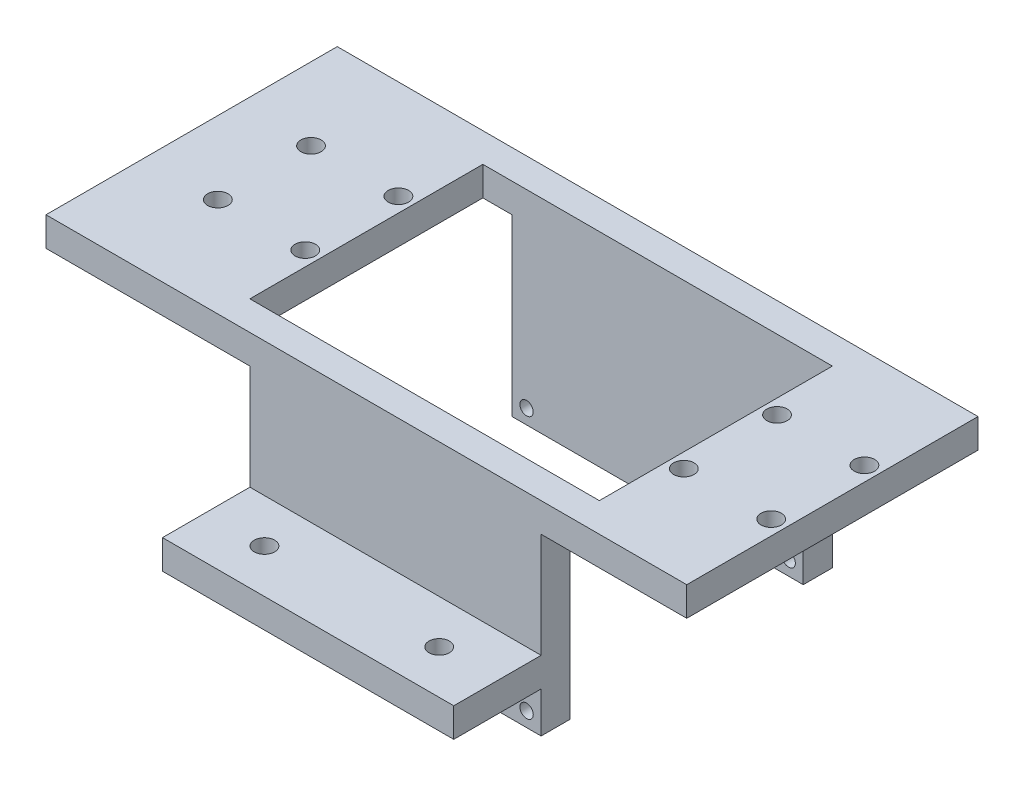
SolidWorks part; units mm, degrees
ref_plane "Front Plane" through (0, 0, 0) normal (0, 0, 1) x (1, 0, 0)
ref_plane "Top Plane" through (0, 0, 0) normal (0, 1, 0) x (1, 0, 0)
ref_plane "Right Plane" through (0, 0, 0) normal (1, 0, 0) x (0, 0, -1)
sketch "Sketch3" plane through (0, 0, 0) normal (0, 1, 0) x (1, 0, 0)
  line L0 (-47.5, 8) -> (-32.5, 8) construction
  line L1 (-50, 25) -> (50, 25)
  line L2 (-50, 25) -> (-50, -25)
  line L3 (-50, -25) -> (50, -25)
  line L4 (50, 25) -> (50, -25)
  line L5 (-50, 25) -> (50, -25) construction
  line L6 (-50, -25) -> (50, 25) construction
  line L7 (-32.5, 8) -> (-32.5, -8) construction
  line L8 (-32.5, -8) -> (-47.5, -8) construction
  line L9 (-47.5, -8) -> (-47.5, 8) construction
  line L10 (-47.5, 0) -> (-32.5, 0) construction
  line L11 (-40, 8) -> (-40, -8) construction
  line L12 (0, -55) -> (0, 55) construction
  line L13 (-30, 25) -> (-30, -25) construction
  line L14 (30, -25) -> (30, 25) construction
  line L15 (32.5, 8) -> (47.5, 8) construction
  circle A0 centre (-47.5, 8) radius 1.75
  circle A1 centre (-32.5, 8) radius 1.75
  circle A2 centre (-47.5, -8) radius 1.75
  circle A3 centre (-32.5, -8) radius 1.75
  circle A4 centre (47.5, -8) radius 1.75
  circle A5 centre (47.5, 8) radius 1.75
  circle A6 centre (32.5, 8) radius 1.75
  circle A7 centre (32.5, -8) radius 1.75
  point P0 (0, 0)
  point P32 (40, 8)
  dimension "D1" = 16
  dimension "D5" = 3.5
  dimension "D2" = 15
  dimension "D3" = 10
  dimension "D4" = 10
  dimension "D6" = 50
  dimension "D7" = 10
  dimension "D8" = 30
extrude "Boss-Extrude1" add sketch "Sketch3" along normal blind 5
sketch "Sketch4" plane through (0, 5, 0) normal (0, 1, 0) x (1, 0, 0)
  line L0 (-50, 25) -> (-50, -25) construction
  line L1 (-30, -20) -> (30, -20)
  line L2 (-30, -20) -> (-30, 20)
  line L3 (-30, 20) -> (30, 20)
  line L4 (30, -20) -> (30, 20)
  line L5 (-30, -20) -> (30, 20) construction
  line L6 (-30, 20) -> (30, -20) construction
  line L7 (50, 25) -> (-50, 25) construction
  point P0 (0, 0)
  dimension "D1" = 20
  dimension "D2" = 5
extrude "Cut-Extrude1" cut sketch "Sketch4" against normal through all and the other way through all
sketch "Sketch5" plane through (0, 0, 0) normal (0, 1, 0) x (1, 0, 0)
  line L0 (50, 25) -> (-50, 25) construction
  line L1 (-25, 25) -> (25, 25)
  line L2 (-25, 25) -> (-25, 20)
  line L3 (-25, 20) -> (25, 20)
  line L4 (25, 25) -> (25, 20)
  line L5 (30, 20) -> (-30, 20) construction
  line L6 (-50, -25) -> (50, -25) construction
  line L7 (-25, -25) -> (25, -25)
  line L8 (-25, -25) -> (-25, -20)
  line L9 (-25, -20) -> (25, -20)
  line L10 (25, -25) -> (25, -20)
  line L11 (-30, -20) -> (30, -20) construction
  line L12 (-50, 25) -> (-50, -25) construction
  line L13 (50, -25) -> (50, 25) construction
  dimension "D1" = 25
  dimension "D2" = 25
extrude "Boss-Extrude2" add sketch "Sketch5" against normal blind 30
sketch "Sketch6" plane through (0, 0, 25) normal (0, 0, 1) x (1, 0, 0)
  line L0 (-25, -30) -> (-25, 0) construction
  line L1 (-25, -18) -> (25, -18)
  line L2 (-25, -18) -> (-25, -23)
  line L3 (-25, -23) -> (25, -23)
  line L4 (25, -18) -> (25, -23)
  line L5 (25, -30) -> (25, 0) construction
  line L6 (-25, -30) -> (25, -30) construction
  dimension "D1" = 5
  dimension "D2" = 7
extrude "Boss-Extrude3" add sketch "Sketch6" along normal blind 15
sketch "Sketch7" plane through (0, -18, 0) normal (0, 1, 0) x (1, 0, 0)
  line L3 (-15, -32.5) -> (15, -32.5) construction
  line L4 (25, -25) -> (-25, -25) construction
  line L5 (0, -40) -> (0, -25) construction
  line L6 (25, -40) -> (-25, -40) construction
  circle A0 centre (-15, -32.5) radius 1.75
  circle A1 centre (15, -32.5) radius 1.75
  point P5 (0, -32.5)
  dimension "D1" = 3.5
  dimension "D2" = 30
extrude "Cut-Extrude2" cut sketch "Sketch7" against normal through all
mirror "Mirror1" about plane through (0, 0, 0) normal (0, 0, 1) of "Cut-Extrude2", "Boss-Extrude3"
sketch "Sketch8" plane through (0, 0, 25) normal (0, 0, 1) x (1, 0, 0)
  line L0 (-22.5, -27.5) -> (22.5, -27.5) construction
  line L1 (0, -30) -> (0, -27.5) construction
  line L4 (-25, -30) -> (25, -30) construction
  line L5 (-25, -30) -> (-25, -23) construction
  circle A0 centre (-22.5, -27.5) radius 1.15
  circle A1 centre (22.5, -27.5) radius 1.15
  dimension "D1" = 2.3
  dimension "D2" = 2.3
  dimension "D3" = 2.5
  dimension "D4" = 2.5
extrude "Cut-Extrude3" cut sketch "Sketch8" against normal through all
sketch "Sketch9" plane through (-50, 0, 0) normal (-1, 0, 0) x (0, 0, 1)
  line L1 (-25, 5) -> (25, 5)
  line L2 (-25, 5) -> (-25, 0)
  line L3 (-25, 0) -> (25, 0)
  line L4 (25, 5) -> (25, 0)
extrude "Boss-Extrude4" add sketch "Sketch9" along normal blind 10
